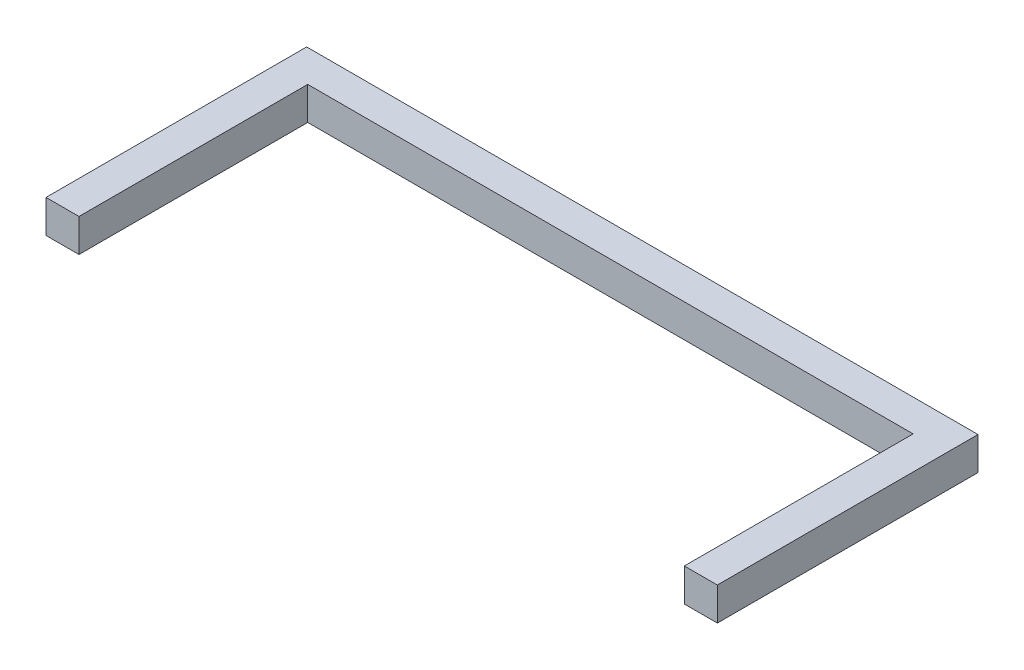
SolidWorks part; units mm, degrees
ref_plane "Front Plane" through (0, 0, 0) normal (0, 0, 1) x (1, 0, 0)
ref_plane "Top Plane" through (0, 0, 0) normal (0, 1, 0) x (1, 0, 0)
ref_plane "Right Plane" through (0, 0, 0) normal (1, 0, 0) x (0, 0, -1)
sketch "Sketch1" plane through (0, 0, 0) normal (0, 1, 0) x (1, 0, 0)
  line L0 (0, 0) -> (0, 24.5)
  line L1 (0, 24.5) -> (63.1, 24.5)
  line L2 (63.1, 24.5) -> (63.1, 0)
  line L3 (63.1, 0) -> (60, 0)
  line L4 (60, 0) -> (60, 21.5)
  line L5 (60, 21.5) -> (3.1, 21.5)
  line L6 (3.1, 21.5) -> (3.1, 0)
  line L7 (3.1, 0) -> (0, 0)
  line L8 (66.85, 1.5) -> (-3.15, 1.5) construction
  dimension "D1" = 3.1
  dimension "D2" = 63.1
  dimension "D3" = 3.1
  dimension "D4" = 3
  dimension "D5" = 20
extrude "Boss-Extrude1" add sketch "Sketch1" along normal blind 3.1
